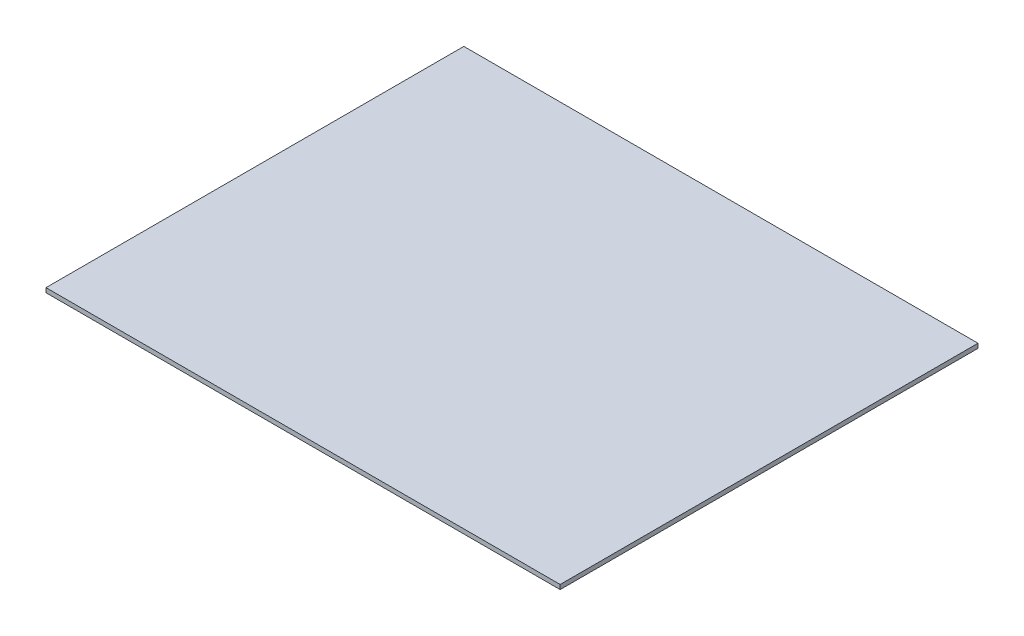
SolidWorks part; units mm, degrees
material "Silício"
ref_plane "Plano frontal" through (0, 0, 0) normal (0, 0, 1) x (1, 0, 0)
ref_plane "Plano superior" through (0, 0, 0) normal (0, 1, 0) x (1, 0, 0)
ref_plane "Plano direito" through (0, 0, 0) normal (1, 0, 0) x (0, 0, -1)
sketch "Esboço1" plane through (0, 0, 0) normal (0, 1, 0) x (1, 0, 0)
  line L0 (-251.5299, 0) -> (251.5299, 0) construction
  line L1 (0, -210.4513) -> (0, 210.4513) construction
  line L2 (173.5, 141) -> (-173.5, 141)
  line L3 (-173.5, 141) -> (-173.5, -141)
  line L4 (173.5, -141) -> (-173.5, -141)
  line L5 (173.5, 141) -> (173.5, -141)
  dimension "D1" = 282
  dimension "D2" = 347
extrude "Ressalto-extrusão1" add sketch "Esboço1" along normal blind 3
